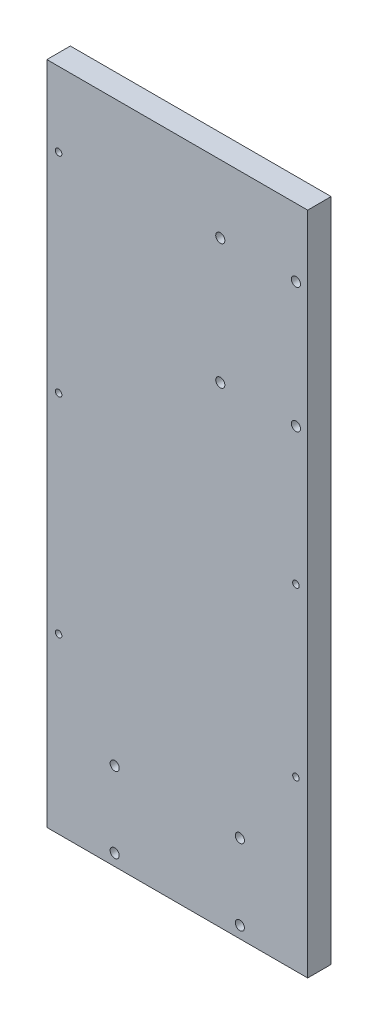
SolidWorks part; units mm, degrees
ref_plane "Front Plane" through (0, 0, 0) normal (0, 0, 1) x (1, 0, 0)
ref_plane "Top Plane" through (0, 0, 0) normal (0, 1, 0) x (1, 0, 0)
ref_plane "Right Plane" through (0, 0, 0) normal (1, 0, 0) x (0, 0, -1)
sketch "Sketch1" plane through (0, 0, 0) normal (0, 0, 1) x (1, 0, 0)
  line L1 (-100, 255) -> (100, 255)
  line L2 (-100, 255) -> (-100, -255)
  line L3 (-100, -255) -> (100, -255)
  line L4 (100, 255) -> (100, -255)
  line L5 (-100, 255) -> (100, -255) construction
  line L6 (-100, -255) -> (100, 255) construction
  point P0 (0, 0)
  dimension "D1" = 510
  dimension "D2" = 200
extrude "Boss-Extrude1" add sketch "Sketch1" along normal blind 18
hole_wizard "Ø7.0 (7) Diameter Hole1" positions "Sketch3" profile "Sketch2" hole size "Ø7.0" standard "ISO" end condition through all
sketch "Sketch3" plane through (0, 0, 18) normal (0, 0, 1) x (1, 0, 0)
  line L0 (100, -255) -> (100, 255) construction
  line L1 (24, 55) -> (24, 255) construction
  line L3 (100, 255) -> (-100, 255) construction
  point P0 (33, 203)
  point P2 (33, 107)
  point P4 (91, 203)
  point P6 (91, 107)
  dimension "D1" = 9
  dimension "D2" = 9
  dimension "D3" = 9
  dimension "D4" = 9
  dimension "D5" = 96
  dimension "D6" = 52
  dimension "D7" = 96
  dimension "D8" = 52
sketch "Sketch2" plane through (33, 203, 18) normal (1, 0, 0) x (0, -1, 0)
  line L0 (0, 0) -> (0, 18)
  line L1 (0, 18) -> (3.5, 18)
  line L2 (3.5, 18) -> (3.5, 0)
  line L5 (3.5, 0) -> (0, 0)
  line L11 (0, -6.35) -> (0, 107.95) construction
  dimension "Thru Hole Dia." = 7
  dimension "Thru Hole Depth" = 18
hole_wizard "Ø5.0 (5) Diameter Hole1" positions "Sketch8" profile "Sketch6" hole size "Ø5.0" standard "ISO" end condition through all
sketch "Sketch8" plane through (0, 0, 18) normal (0, 0, 1) x (1, 0, 0)
  line L0 (-100, 255) -> (-100, -255) construction
  line L1 (-82, -179) -> (-100, -179) construction
  point P2 (-91, 198)
  point P4 (-91, 38)
  point P6 (-91, -122)
  dimension "D1" = 160
  dimension "D2" = 9
  dimension "D3" = 9
  dimension "D4" = 9
  dimension "D5" = 160
  dimension "D6" = 57
sketch "Sketch6" plane through (-91, 198, 18) normal (1, 0, 0) x (0, -1, 0)
  line L0 (0, 0) -> (0, 18)
  line L1 (0, 18) -> (2.5, 18)
  line L2 (2.5, 18) -> (2.5, 0)
  line L5 (2.5, 0) -> (0, 0)
  line L11 (0, -6.35) -> (0, 107.95) construction
  dimension "Thru Hole Dia." = 5
  dimension "Thru Hole Depth" = 18
hole_wizard "Ø5.0 (5) Diameter Hole2" positions "Sketch10" profile "Sketch9" hole size "Ø5.0" standard "ISO" end condition through all
sketch "Sketch10" plane through (0, 0, 18) normal (0, 0, 1) x (1, 0, 0)
  line L0 (100, -255) -> (100, 255) construction
  line L1 (-100, -179) -> (100, -179) construction
  point P0 (91, 2)
  point P2 (91, -126)
  dimension "D1" = 9
  dimension "D2" = 9
  dimension "D3" = 128
  dimension "D4" = 53
sketch "Sketch9" plane through (91, 2, 18) normal (1, 0, 0) x (0, -1, 0)
  line L0 (0, 0) -> (0, 18)
  line L1 (0, 18) -> (2.5, 18)
  line L2 (2.5, 18) -> (2.5, 0)
  line L5 (2.5, 0) -> (0, 0)
  line L11 (0, -6.35) -> (0, 107.95) construction
  dimension "Thru Hole Dia." = 5
  dimension "Thru Hole Depth" = 18
hole_wizard "Ø7.0 (7) Diameter Hole2" positions "Sketch12" profile "Sketch11" hole size "Ø7.0" standard "ISO" end condition through all
sketch "Sketch12" plane through (0, 0, 18) normal (0, 0, 1) x (1, 0, 0)
  point P0 (48, -188)
  point P3 (-48, -188)
  point P6 (48, -246)
  point P9 (-48, -246)
sketch "Sketch11" plane through (48, -188, 18) normal (1, 0, 0) x (0, -1, 0)
  line L0 (0, 0) -> (0, 18)
  line L1 (0, 18) -> (3.5, 18)
  line L2 (3.5, 18) -> (3.5, 0)
  line L5 (3.5, 0) -> (0, 0)
  line L11 (0, -6.35) -> (0, 107.95) construction
  dimension "Thru Hole Dia." = 7
  dimension "Thru Hole Depth" = 18
